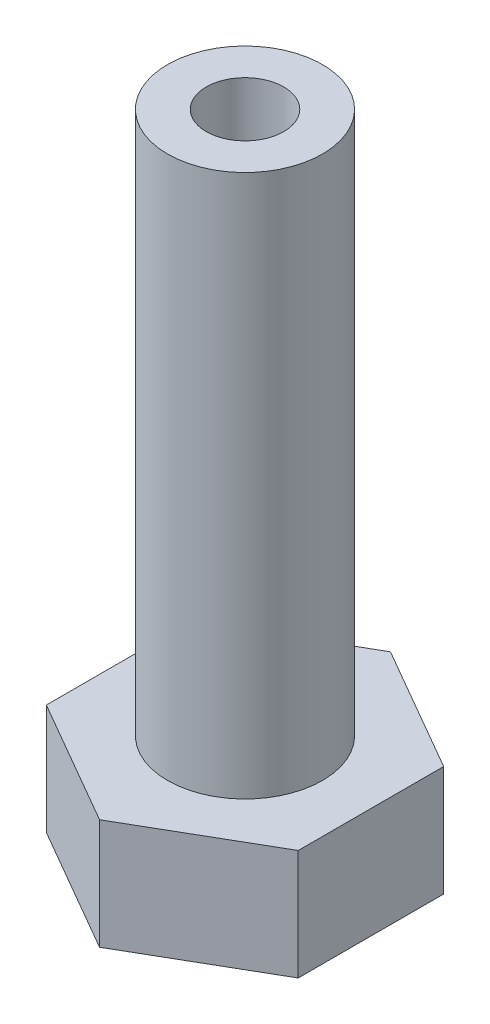
SolidWorks part; units mm, degrees
ref_plane "Front Plane" through (0, 0, 0) normal (0, 0, 1) x (1, 0, 0)
ref_plane "Top Plane" through (0, 0, 0) normal (0, 1, 0) x (1, 0, 0)
ref_plane "Right Plane" through (0, 0, 0) normal (1, 0, 0) x (0, 0, -1)
sketch "Sketch1" plane through (0, 0, 0) normal (0, 1, 0) x (1, 0, 0)
  line L1 (0, -7.5056) -> (6.5, -3.7528)
  line L2 (6.5, -3.7528) -> (6.5, 3.7528)
  line L3 (6.5, 3.7528) -> (0, 7.5056)
  line L4 (0, 7.5056) -> (-6.5, 3.7528)
  line L5 (-6.5, 3.7528) -> (-6.5, -3.7528)
  line L6 (-6.5, -3.7528) -> (0, -7.5056)
  circle A0 centre (0, 0) radius 6.5 construction
  dimension "D1" = 13
extrude "Boss-Extrude1" add sketch "Sketch1" along normal blind 5.7
sketch "Sketch2" plane through (0, 5.7, 0) normal (0, 1, 0) x (1, 0, 0)
  circle A0 centre (0, 0) radius 4
  dimension "D1" = 8
extrude "Boss-Extrude2" add sketch "Sketch2" along normal blind 28
sketch "Sketch3" plane through (0, 33.7, 0) normal (0, 1, 0) x (1, 0, 0)
  circle A0 centre (0, 0) radius 2
  dimension "D1" = 4
extrude "Cut-Extrude1" cut sketch "Sketch3" against normal blind 8
